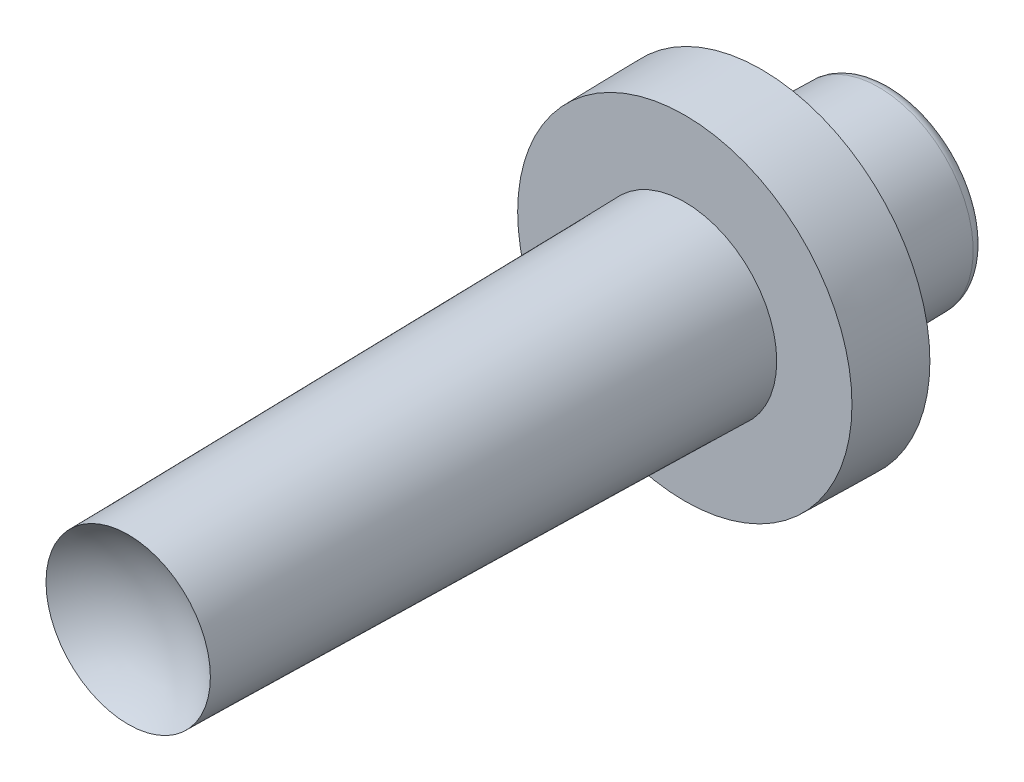
SolidWorks part; units mm, degrees
material "PC High Viscosity"
ref_plane "Front" through (0, 0, 0) normal (0, 0, 1) x (1, 0, 0)
ref_plane "Top" through (0, 0, 0) normal (0, 1, 0) x (1, 0, 0)
ref_plane "Right" through (0, 0, 0) normal (1, 0, 0) x (0, 0, -1)
sketch "Sketch1" plane through (0, 0, 0) normal (0, 0, 1) x (1, 0, 0)
  circle A0 centre (0, 0) radius 2.794
  dimension "D1" = 5.588
extrude "Boss-Extrude1" add sketch "Sketch1" along normal blind 1.27 draft 1
sketch "Sketch2" plane through (0, 0, 1.27) normal (0, 0, 1) x (1, 0, 0)
  circle A0 centre (0, 0) radius 1.524
  dimension "D1" = 3.048
extrude "Boss-Extrude2" add sketch "Sketch2" along normal blind 9.23 draft 1
sketch "Sketch3" plane through (0, 0, 0) normal (0, 0, -1) x (-1, 0, 0)
  circle A0 centre (0, 0) radius 1.6
  dimension "D1" = 3.2
extrude "Boss-Extrude3" add sketch "Sketch3" along normal blind 2.1 draft 1
ref_axis "Axis1" through (0, 0, 1.27) along (0, 0, 1)
ref_plane "Plane1" through (0, 0, 0) normal (0, 1, 0) x (1, 0, 0)
sketch "Sketch5" plane through (0, 0, 0) normal (0, 1, 0) x (1, 0, 0)
  line L0 (0, -10.5) -> (0, -9.9412)
  line L1 (1.3629, -10.5) -> (1.3629, -10.8239)
  line L2 (0, -9.9412) -> (-0.3156, -9.9412) construction
  line L3 (1.3629, -10.8239) -> (0, -10.8239)
  line L4 (0, -10.8239) -> (0, -10.5)
  line L5 (-1.3629, -10.5) -> (1.3629, -10.5) construction
  arc A0 (0, -9.9412) -> (1.3629, -10.5) centre (0, -11.8826) cw
  dimension "D1" = 0.5588
  dimension "D2" = 0.3239
revolve "Cut-Revolve4" cut sketch "Sketch5" angle 360 about axis through (0, 0, 1.27) along (0, 0, 1)
sketch "Sketch6" plane through (0, 0, 0) normal (0, 1, 0) x (1, 0, 0)
  line L0 (0, 2.1) -> (0, 3.7552) construction
  line L1 (1.5633, 2.1) -> (-1.5633, 2.1) construction
  line L2 (0, 2.3) -> (0, 2.1)
  line L3 (0, 2.1) -> (0, -3.9101) construction
  line L4 (0, 2.1) -> (-1.5633, 2.1)
  line L5 (-1.5633, 2.1) -> (-1.6, 0) construction
  arc A0 (-1.5633, 2.1) -> (0, 2.3) centre (0, -3.9101) cw
  dimension "D1" = 0.2
revolve "Revolve1" add sketch "Sketch6" angle 360 about L0
fillet "Fillet1" radius 0.2 1 edges at (-1.5633, 0, -2.1)
